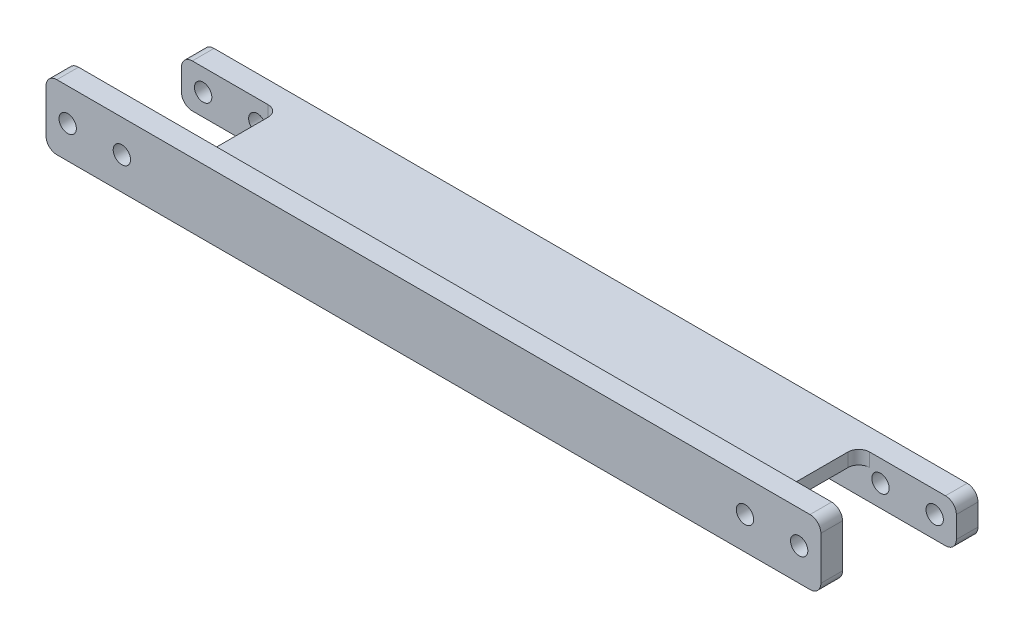
SolidWorks part; units mm, degrees
ref_plane "前视基准面" through (0, 0, 0) normal (0, 0, 1) x (1, 0, 0)
ref_plane "上视基准面" through (0, 0, 0) normal (0, 1, 0) x (1, 0, 0)
ref_plane "右视基准面" through (0, 0, 0) normal (1, 0, 0) x (0, 0, -1)
other "Configuration Table"
sketch "草图1" plane through (0, 0, 0) normal (0, 0, 1) x (1, 0, 0)
  line L1 (-71.5, 4) -> (71.5, 4)
  line L2 (-71.5, 4) -> (-71.5, -4)
  line L3 (-71.5, -4) -> (71.5, -4)
  line L4 (71.5, 4) -> (71.5, -4)
  line L5 (-71.5, 4) -> (71.5, -4) construction
  line L6 (-71.5, -4) -> (71.5, 4) construction
  circle A0 centre (-67.5, 0) radius 1.6
  circle A1 centre (-57.5, 0) radius 1.6
  circle A2 centre (57.5, 0) radius 1.6
  circle A3 centre (67.5, 0) radius 1.6
  point P0 (0, 0)
  point P14 (71.5, 0)
  dimension "D3" = 3.2
  dimension "D5" = 10
  dimension "D6" = 4
  dimension "D7" = 10
  dimension "D1" = 143
  dimension "D2" = 8
  dimension "D4" = 4
extrude "凸台-拉伸1" add sketch "草图1" along normal blind 4
sketch "草图2" plane through (0, 0, 4) normal (0, 0, 1) x (1, 0, 0)
  line L0 (71.5, 4) -> (-71.5, 4) construction
  line L1 (-53.5, 6.5) -> (53.5, 6.5)
  line L2 (-53.5, 6.5) -> (-53.5, 1.5)
  line L3 (-53.5, 1.5) -> (53.5, 1.5)
  line L4 (53.5, 6.5) -> (53.5, 1.5)
  line L5 (-53.5, 6.5) -> (53.5, 1.5) construction
  line L6 (-53.5, 1.5) -> (53.5, 6.5) construction
  line L7 (-53.5, 4) -> (53.5, 4)
  point P0 (0, 4)
  line M6 (71.5, 4) -> (-71.5, 4)
  dimension "D1" = 5
  dimension "D2" = 107
extrude "凸台-拉伸2" add sketch "草图2" along normal blind 21 contours L4 L2 L3 M6
sketch "草图3" plane through (0, 0, 25) normal (0, 0, 1) x (1, 0, 0)
  line L5 (-71.5, 4) -> (-71.5, -4) construction
  line L6 (71.5, 13.5) -> (-71.5, 13.5)
  line L10 (71.5, 13.5) -> (71.5, 1.5)
  line L11 (71.5, 1.5) -> (-71.5, 1.5)
  line L12 (-71.5, 13.5) -> (-71.5, 1.5)
  line L13 (71.5, 13.5) -> (-71.5, 1.5) construction
  line L14 (71.5, 1.5) -> (-71.5, 13.5) construction
  line L15 (-53.5, 1.5) -> (53.5, 1.5) construction
  line L16 (71.5, -4) -> (71.5, 4) construction
  circle A0 centre (67.5, 7.5) radius 1.6
  circle A1 centre (57.5, 7.5) radius 1.6
  circle A2 centre (-67.5, 7.5) radius 1.6
  circle A3 centre (-57.5, 7.5) radius 1.6
  circle A4 centre (-67.5, 0) radius 1.6 construction
  point P0 (0, 7.5)
  point P3 (0, 7.5)
  point P21 (62.8892, 7.4954)
  dimension "D2" = 4
  dimension "D3" = 10
  dimension "D4" = 10
  dimension "D6" = 3.2
  dimension "D7" = 7.5
  dimension "D1" = 7.5
extrude "凸台-拉伸4" add sketch "草图3" along normal blind 4
fillet "圆角1" radius 2 12 edges at (-53.5, 2.75, 25) (53.5, 2.75, 25) (53.5, 2.75, 4) (-53.5, 2.75, 4) (71.5, 4, 2) (-71.5, 4, 2) (71.5, -4, 2) (-71.5, -4, 2) (-71.5, 13.5, 27) (71.5, 13.5, 27) (71.5, 1.5, 27) (-71.5, 1.5, 27)
